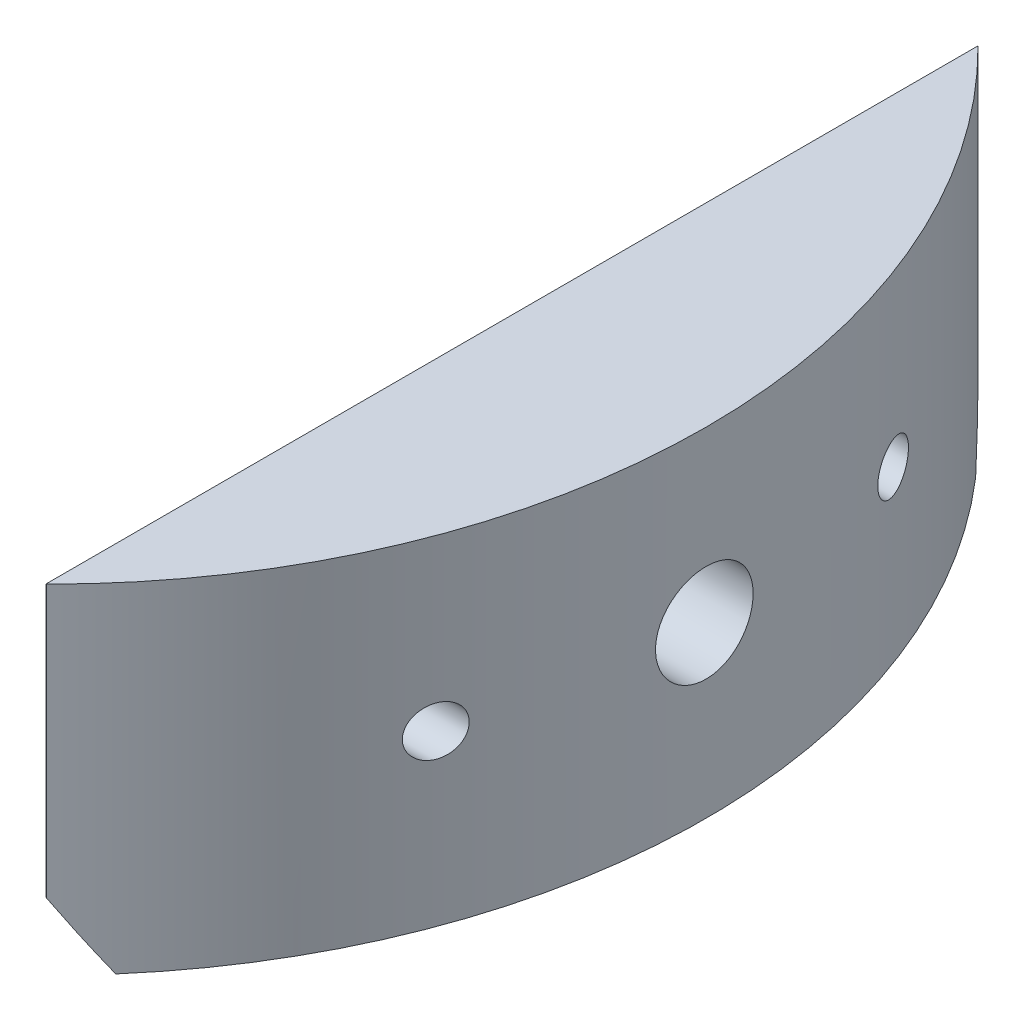
SolidWorks part; units mm, degrees
material "Plain Carbon Steel"
ref_plane "Front Plane" through (0, 0, 0) normal (0, 0, 1) x (1, 0, 0)
ref_plane "Top Plane" through (0, 0, 0) normal (0, 1, 0) x (1, 0, 0)
ref_plane "Right Plane" through (0, 0, 0) normal (1, 0, 0) x (0, 0, -1)
sketch "Sketch2" plane through (0, 0, 0) normal (0, 1, 0) x (1, 0, 0)
  line L0 (34.6715, 34.925) -> (34.6715, -34.925)
  line L2 (34.6715, 34.925) -> (34.6461, 34.925)
  line L3 (34.6715, 34.925) -> (34.6715, -34.925)
  line L4 (34.6715, -34.925) -> (34.6461, -34.925)
  line L5 (34.6461, 34.925) -> (34.6461, -34.925)
  line L13 (0, 0) -> (29.3279, 0) construction
  line L14 (0, 0) -> (47.5356, -12.7371) construction
  arc A0 (34.6715, -34.925) -> (34.6715, 34.925) centre (0, 0) ccw
  point P9 (34.6461, 0)
  dimension "D1" = 49.2125
  dimension "D2" = 69.85
  dimension "D3" = 0.0254
  dimension "D6" = 15
extrude "Boss-Extrude1" add sketch "Sketch2" along normal blind 25.4
ref_plane "Plane1" through (49.2125, 0, 0) normal (1, 0, 0) x (0, 0, -1)
sketch "Sketch4" plane through (34.6461, 0, 0) normal (-1, 0, 0) x (0, 0, 1)
  line L0 (-34.925, 12.7) -> (34.925, 12.7) construction
  line L1 (-34.925, 25.4) -> (-34.925, 0) construction
  line L2 (0, 25.4) -> (0, 0) construction
  line L4 (-34.925, 0) -> (34.925, 0)
  line L10 (34.925, 0) -> (34.925, 25.4)
  line L11 (34.925, 25.4) -> (-34.925, 25.4)
  line L12 (-34.925, 25.4) -> (-34.925, 0)
  line L13 (-34.925, 0) -> (34.925, 0)
  line L14 (34.925, 0) -> (34.925, 25.4)
  line L15 (34.925, 25.4) -> (-34.925, 25.4)
  line L16 (-34.925, 25.4) -> (-34.925, 0)
  circle A0 centre (0, 12.7) radius 3.81
  circle A1 centre (0, 12.7) radius 1.27
  point P15 (0, 12.7)
  dimension "D1" = 7.62
  dimension "D2" = 2.54
  dimension "D3" = 0
extrude "Cut-Extrude2" cut sketch "Sketch4" against normal up to next contours A1
sketch "Sketch11" plane through (34.6461, 0, 0) normal (-1, 0, 0) x (0, 0, 1)
  circle A2 centre (0, 12.7) radius 3.6576
  dimension "D3" = 7.3152
extrude "Cut-Extrude4" cut sketch "Sketch11" along normal blind 7.62 from surface at -14.5664 contours A2 starting at plane "Plane1"
sketch "Sketch13" plane through (49.2125, 0, 0) normal (1, 0, 0) x (0, 0, -1)
  line L1 (-6.2992, 12.7) -> (-7.6327, 12.7) construction
  line L2 (-6.2992, 12.7) -> (-4.9657, 12.7) construction
  line L4 (0, 12.7) -> (-34.925, 12.7) construction
  line L5 (-34.925, 25.4) -> (-34.925, 0) construction
  circle A0 centre (0, 12.7) radius 4.9657
  circle A1 centre (0, 12.7) radius 7.6327
  circle A2 centre (0, 12.7) radius 6.2992 construction
  dimension "D1" = 12.5984
  dimension "D2" = 2.667
wrap "Wrap3" [suppressed] sketch "Sketch13" source sketch "Sketch13" thickness 1.3208 parameters "D1"=1.3208
sketch "Sketch15" plane through (0, 0, 0) normal (1, 0, 0) x (0, 0, -1)
  line L0 (-34.925, 12.7) -> (34.925, 12.7) construction
  line L1 (0, 0) -> (0, 25.4) construction
  line L4 (-34.925, 0) -> (34.925, 0)
  line L5 (34.925, 0) -> (34.925, 25.4)
  line L6 (-34.925, 0) -> (34.925, 0)
  line L7 (-34.925, 25.4) -> (-34.925, 0)
  line L9 (34.925, 0) -> (34.925, 25.4)
  line L11 (-34.925, 25.4) -> (-34.925, 0)
  line L14 (34.925, 25.4) -> (-34.925, 25.4)
  line L15 (34.925, 25.4) -> (-34.925, 25.4)
  circle A0 centre (-17.145, 12.7) radius 1.8288
  circle A1 centre (17.145, 12.7) radius 1.8288
  dimension "D2" = 3.6576
  dimension "D3" = 17.145
  dimension "D1" = 0
extrude "Cut-Extrude5" cut sketch "Sketch15" along normal up to surface (46.7684 mm away) contours L0 A0 | A1
chamfer "Chamfer1" distance 2.54 distance2 5.08 1 edges at (34.6461, 0, 0)
equation "\"Middle Coupler Inner Daimeter\"= 3.875in"
equation "\"Middle Coupler  Wall Thickness\" = 0.25in"
equation "\"Middle Coupler Bottom Thickness\"= 0.2in"
equation "\"Bearing Rail Offset\"= 0.45in"
equation "\"3-56 UNF Tap\"= 0.089in"
equation "\"3-48 Tap\"= 0.079in"
equation "\"3-56 UNF Clearance\"= 0.104in"
equation "\"3-48 Clearance\" = 0.104in"
equation "\"Ball Bearing Distance\"= 0.03in"
equation "\"TCA Outer Diameter\" = 6in"
equation "\"Interstage Aeroframe Wall Thickness\" = 0.072in"
equation "\"Compression Spring OD\"= 0.42in"
equation "\"10-24 Tap\"= 0.1495in"
equation "\"10-24 Clearance\"= 0.196in"
equation "\"Lower Stage Fuselage Wall Thickness\" = 0.25in"
equation "\"6-32 Tap\" = 0.107in"
equation "\"6-32 Clearance\" = 0.144in"
equation "\"1/4-20 Tap\" = 0.201in"
equation "\"12-24 Tap\" = 0.177in"
equation "\"D1@Sketch2\"=\"Middle Coupler Inner Daimeter\"/2"
equation "\"D2@Sketch15\"=\"6-32 Clearance\""
